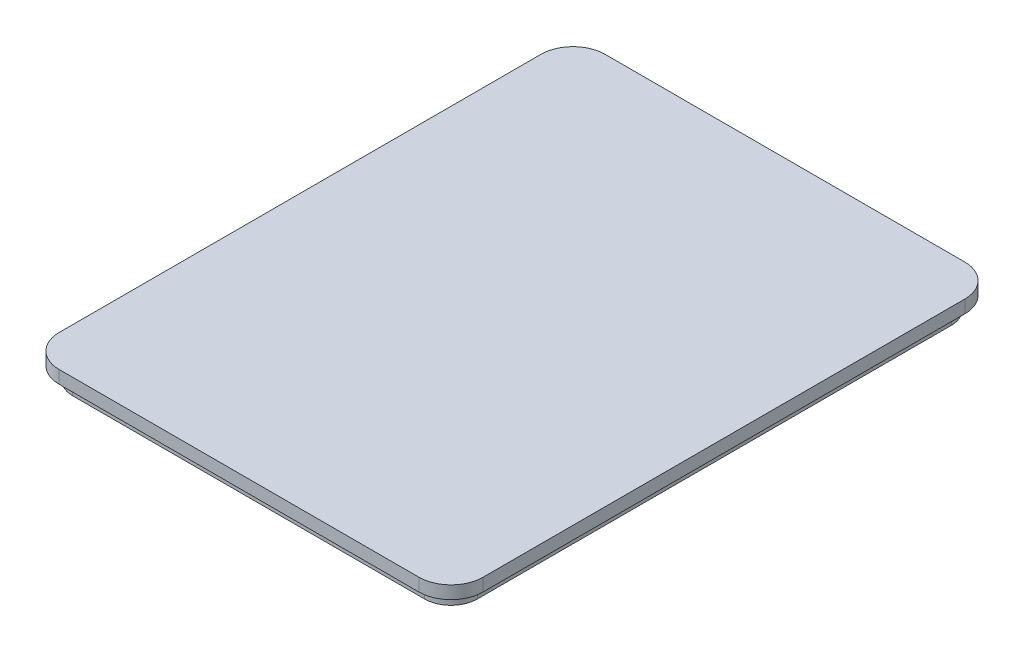
SolidWorks part; units mm, degrees
ref_plane "Piano frontale" through (0, 0, 0) normal (0, 0, 1) x (1, 0, 0)
ref_plane "Piano superiore" through (0, 0, 0) normal (0, 1, 0) x (1, 0, 0)
ref_plane "Piano destro" through (0, 0, 0) normal (1, 0, 0) x (0, 0, -1)
sketch "Schizzo1" plane through (0, 0, 0) normal (0, 1, 0) x (1, 0, 0)
  line L1 (5, 0) -> (61, 0)
  line L2 (0, 5) -> (0, 80)
  line L3 (5, 85) -> (61, 85)
  line L4 (66, 5) -> (66, 80)
  arc A0 (0, 5) -> (5, 0) centre (5, 5) ccw
  arc A1 (61, 0) -> (66, 5) centre (61, 5) ccw
  arc A2 (66, 80) -> (61, 85) centre (61, 80) ccw
  arc A3 (5, 85) -> (0, 80) centre (5, 80) ccw
  point P7 (0, 0)
  point P10 (66, 0)
  point P13 (66, 85)
  dimension "D3" = 5
  dimension "D1" = 66
  dimension "D2" = 85
extrude "Estrusione-Estrusione1" add sketch "Schizzo1" along normal blind 2
sketch "Schizzo2" plane through (0, 0, 0) normal (0, -1, 0) x (1, 0, 0)
  line L0 (66, -5) -> (66, -80) construction
  line L1 (60.3939, -83.5) -> (5.6061, -83.5)
  line L2 (64.5, -79.3939) -> (64.5, -5.6061)
  line L3 (60.3939, -1.5) -> (5.6061, -1.5)
  line L4 (1.5, -79.3939) -> (1.5, -5.6061)
  line L5 (64.5, -83.5) -> (1.5, -1.5) construction
  line L6 (64.5, -1.5) -> (1.5, -83.5) construction
  line L7 (0, -80) -> (0, -5) construction
  line L8 (61, -85) -> (5, -85) construction
  line L9 (5, 0) -> (61, 0) construction
  arc A0 (64.5, -5.6061) -> (60.3939, -1.5) centre (60.3939, -5.6061) ccw
  arc A1 (5.6061, -1.5) -> (1.5, -5.6061) centre (5.6061, -5.6061) ccw
  arc A2 (1.5, -79.3939) -> (5.6061, -83.5) centre (5.6061, -79.3939) ccw
  arc A3 (64.5, -79.3939) -> (60.3939, -83.5) centre (60.3939, -79.3939) cw
  point P0 (33, -42.5)
  dimension "D5" = 4.1061
  dimension "D1" = 1.5
  dimension "D2" = 1.5
  dimension "D3" = 1.5
  dimension "D4" = 1.5
extrude "Estrusione-Estrusione2" add sketch "Schizzo2" along normal blind 2
